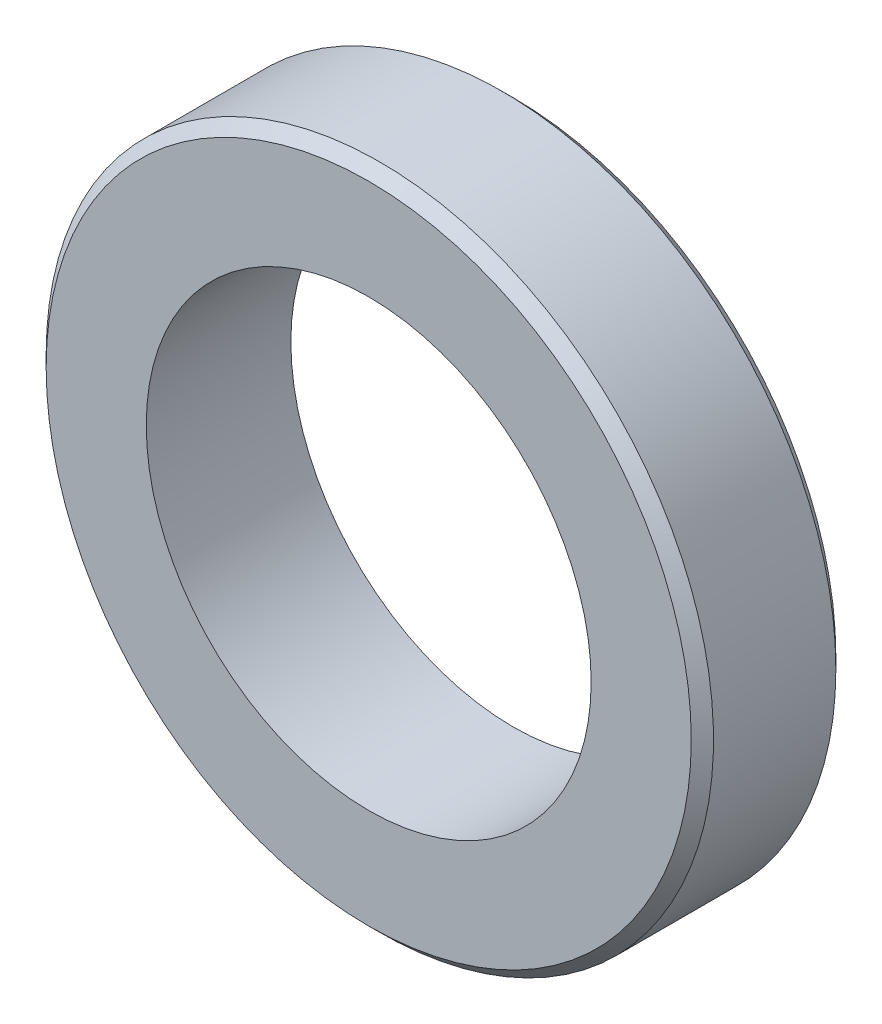
SolidWorks part; units mm, degrees
material "1060-H12 棒材(SS)"
ref_plane "前视基准面" through (0, 0, 0) normal (0, 0, 1) x (1, 0, 0)
ref_plane "上视基准面" through (0, 0, 0) normal (0, 1, 0) x (1, 0, 0)
ref_plane "右视基准面" through (0, 0, 0) normal (1, 0, 0) x (0, 0, -1)
sketch "草图1" plane through (0, 0, 0) normal (0, 0, 1) x (1, 0, 0)
  circle A0 centre (0, 0) radius 20
  circle A1 centre (0, 0) radius 30
  dimension "D1" = 40
  dimension "D2" = 60
extrude "凸台-拉伸1" add sketch "草图1" along normal blind 13
chamfer "倒角1" distance 1 angle 45 2 edges at (30, 0, 13) (30, 0, 0)
